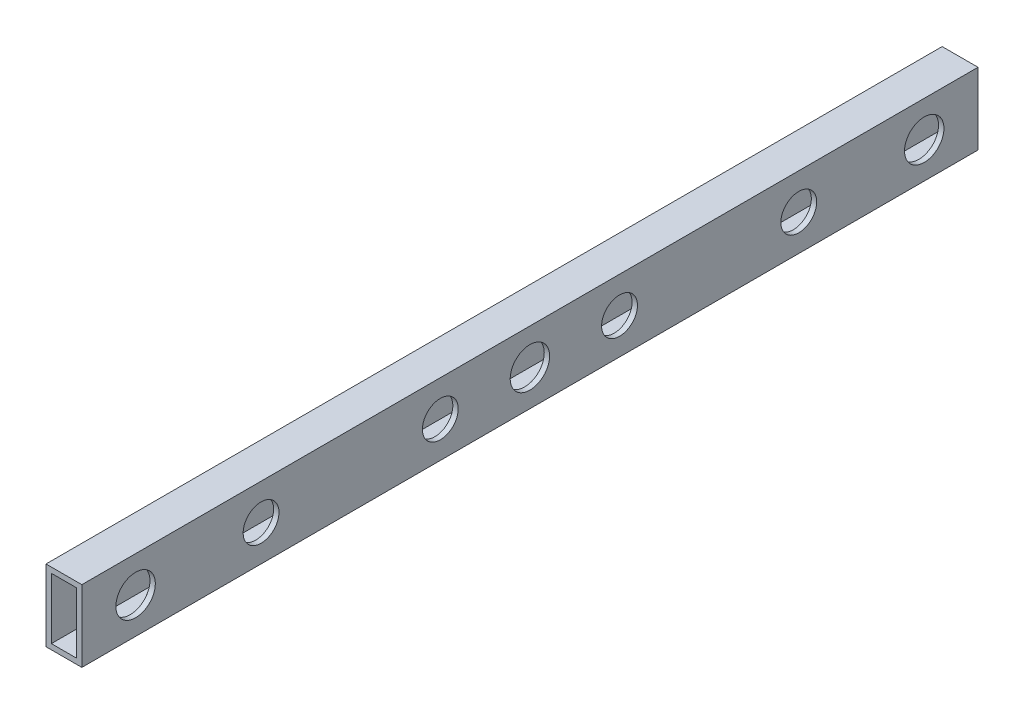
SolidWorks part; units mm, degrees
material "Д16Т ГОСТ 4784-74"
ref_plane "Спереди" through (0, 0, 0) normal (0, 0, 1) x (1, 0, 0)
ref_plane "Сверху" through (0, 0, 0) normal (0, 1, 0) x (1, 0, 0)
ref_plane "Справа" through (0, 0, 0) normal (1, 0, 0) x (0, 0, -1)
sketch "Эскиз1" plane through (0, 0, 0) normal (0, 0, 1) x (1, 0, 0)
  line L1 (0, 0) -> (10, 0)
  line L2 (0, 0) -> (0, 20)
  line L3 (0, 20) -> (10, 20)
  line L4 (10, 0) -> (10, 20)
  dimension "D1" = 20
  dimension "D2" = 10
extrude "Вытянуть-Тонкостенный1" add sketch "Эскиз1" along normal blind 250 thin thin type one direction reverse wall 1.5
hole_wizard "Цековка для  винта с внутренним шестигранником M61" positions "Эскиз3" profile "Эскиз2" counterbore size "M6" standard "DIN" end condition through all
sketch "Эскиз3" plane through (10, 0, 0) normal (1, 0, 0) x (0, 0, -1)
  line L0 (-250, 10) -> (-235, 10)
  line L1 (-250, 0) -> (-250, 20) construction
  point P0 (-235, 10)
  point P11 (-125, 10)
  point P12 (-15, 10)
  dimension "D1" = 15
  dimension "D2" = 3
sketch "Эскиз2" plane through (10, 10, 235) normal (0, 1, 0) x (0, 0, -1)
  line L0 (0, 0) -> (0, 10)
  line L1 (0, 10) -> (3.3, 10)
  line L3 (3.3, 10) -> (3.3, 6.4)
  line L4 (3.3, 6.4) -> (5.5, 6.4)
  line L5 (5.5, 6.4) -> (5.5, 0)
  line L7 (5.5, 0) -> (0, 0)
  line L11 (0, -6.35) -> (0, 107.95) construction
  dimension "Диаметр сквозного отверстия" = 6.6
  dimension "Глубина сквозного отверстия" = 10
  dimension "Диаметр цековки" = 11
  dimension "Глубина цековки" = 6.4
hole_wizard "Отверстие1" positions "Эскиз5" profile "Эскиз4" legacy
sketch "Эскиз5" plane through (0, 0, 0) normal (-1, 0, 0) x (0, 0, 1)
  line L0 (50, 10) -> (0, 10)
  line L1 (0, 20) -> (0, 0) construction
  line L3 (125, 20) -> (125, 0) construction
  line L4 (250, 20) -> (0, 20) construction
  line L5 (250, 0) -> (0, 0) construction
  point P0 (50, 10)
  point P16 (100, 10)
  point P21 (150, 10)
  point P22 (200, 10)
  dimension "D1" = 50
  dimension "D2" = 50
sketch "Эскиз4" plane through (0, 10, 50) normal (0, 1, 0) x (0, 0, 1)
  line L0 (0, 0) -> (0, 100)
  line L1 (0, 100) -> (5, 100)
  line L2 (5, 100) -> (5, 0)
  line L3 (5, 0) -> (0, 0)
  line L4 (0, 110) -> (0, -10) construction
  dimension "Диаметр" = 10
  dimension "Глубина" = 100
